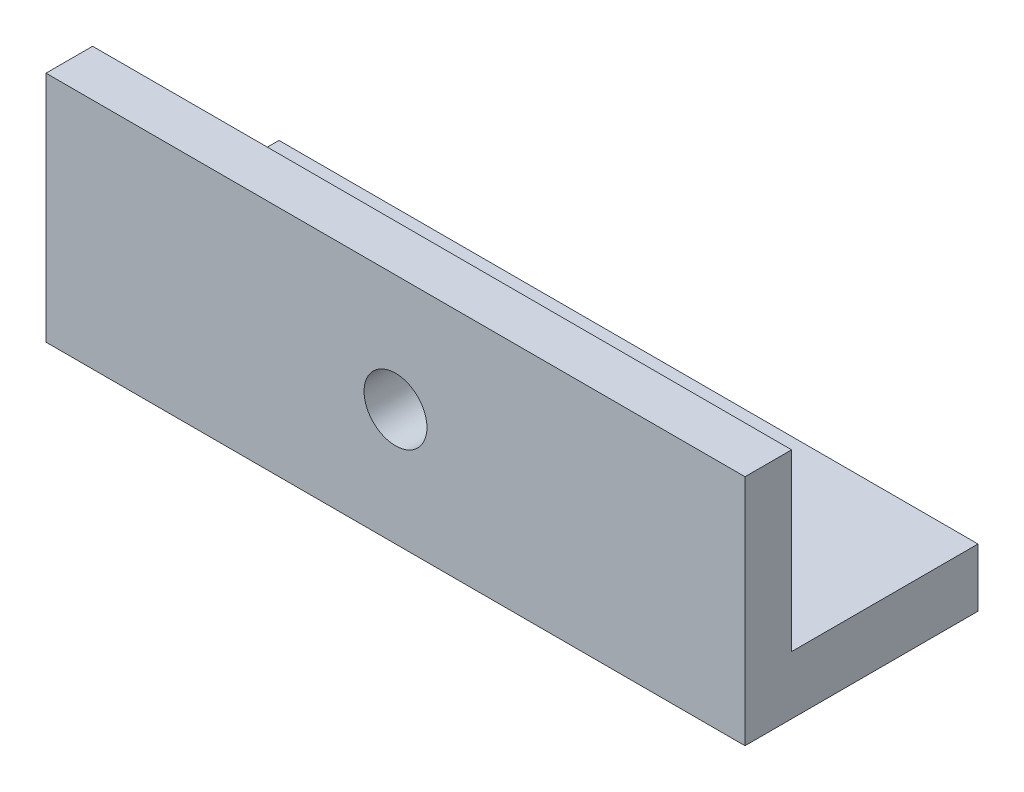
SolidWorks part; units mm, degrees
ref_plane "Front" through (0, 0, 0) normal (0, 0, 1) x (1, 0, 0)
ref_plane "Top" through (0, 0, 0) normal (0, 1, 0) x (1, 0, 0)
ref_plane "Right" through (0, 0, 0) normal (1, 0, 0) x (0, 0, -1)
sketch "Sketch1" plane through (0, 0, 0) normal (0, 1, 0) x (1, 0, 0)
  line L1 (0, 0) -> (76.2, 0)
  line L2 (0, 0) -> (0, 25.4)
  line L3 (0, 25.4) -> (76.2, 25.4)
  line L4 (76.2, 0) -> (76.2, 25.4)
  circle A0 centre (63.5, 12.7) radius 2.794
  circle A1 centre (12.7, 12.7) radius 2.794
  dimension "D3" = 5.588
  dimension "D4" = 5.588
  dimension "D1" = 76.2
  dimension "D2" = 25.4
  dimension "D5" = 12.7
  dimension "D6" = 12.7
  dimension "D7" = 12.7
  dimension "D8" = 12.7
extrude "Boss-Extrude1" add sketch "Sketch1" along normal blind 6.35
sketch "Sketch2" plane through (0, 6.35, 0) normal (0, 1, 0) x (1, 0, 0)
  line L0 (76.2, 0) -> (76.2, 25.4) construction
  line L1 (0, 0) -> (76.2, 0)
  line L2 (0, 0) -> (0, 5.08)
  line L3 (0, 5.08) -> (76.2, 5.08)
  line L4 (76.2, 0) -> (76.2, 5.08)
  dimension "D1" = 5.08
extrude "Boss-Extrude2" add sketch "Sketch2" along normal blind 19.05
sketch "Sketch3" plane through (0, 0, 0) normal (0, 0, 1) x (1, 0, 0)
  line L0 (0, 25.4) -> (76.2, 25.4) construction
  circle A0 centre (38.1, 12.7) radius 3.429
  dimension "D1" = 12.7
extrude "Cut-Extrude1" cut sketch "Sketch3" against normal up to surface (5.08 mm away) up to face at (38.1, 15.875, -5.08)
